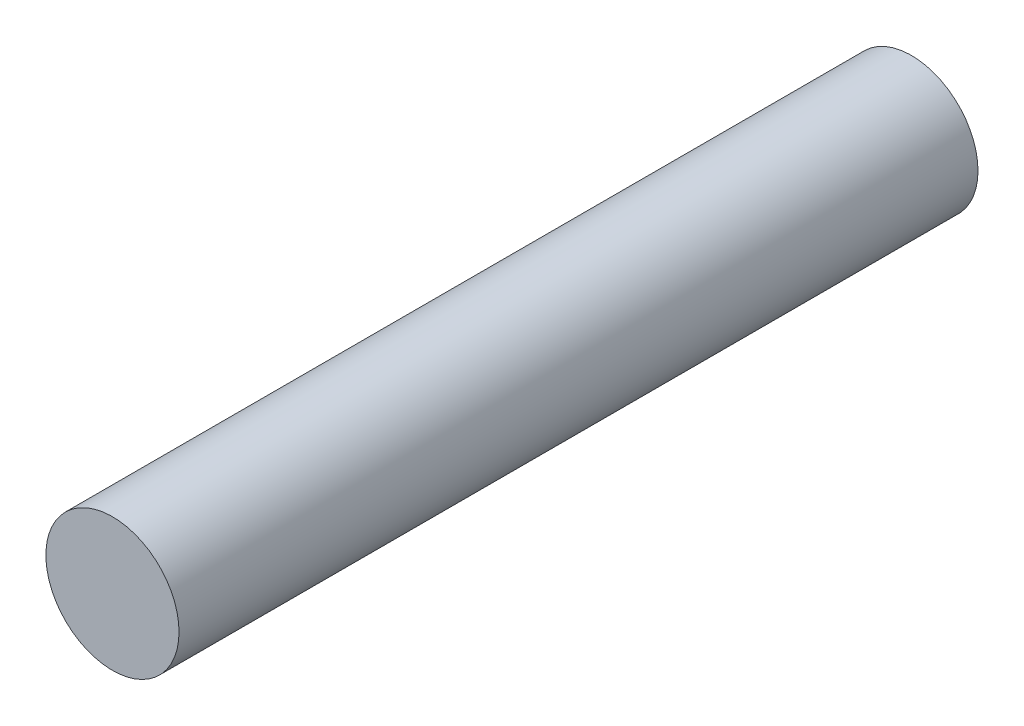
SolidWorks part; units mm, degrees
ref_plane "Front Plane" through (0, 0, 0) normal (0, 0, 1) x (1, 0, 0)
ref_plane "Top Plane" through (0, 0, 0) normal (0, 1, 0) x (1, 0, 0)
ref_plane "Right Plane" through (0, 0, 0) normal (1, 0, 0) x (0, 0, -1)
sketch "Sketch1" plane through (0, 0, 0) normal (0, 0, 1) x (1, 0, 0)
  circle A0 centre (0, 0) radius 12.5
  dimension "D1" = 25
extrude "Boss-Extrude1" add sketch "Sketch1" along normal blind 150
